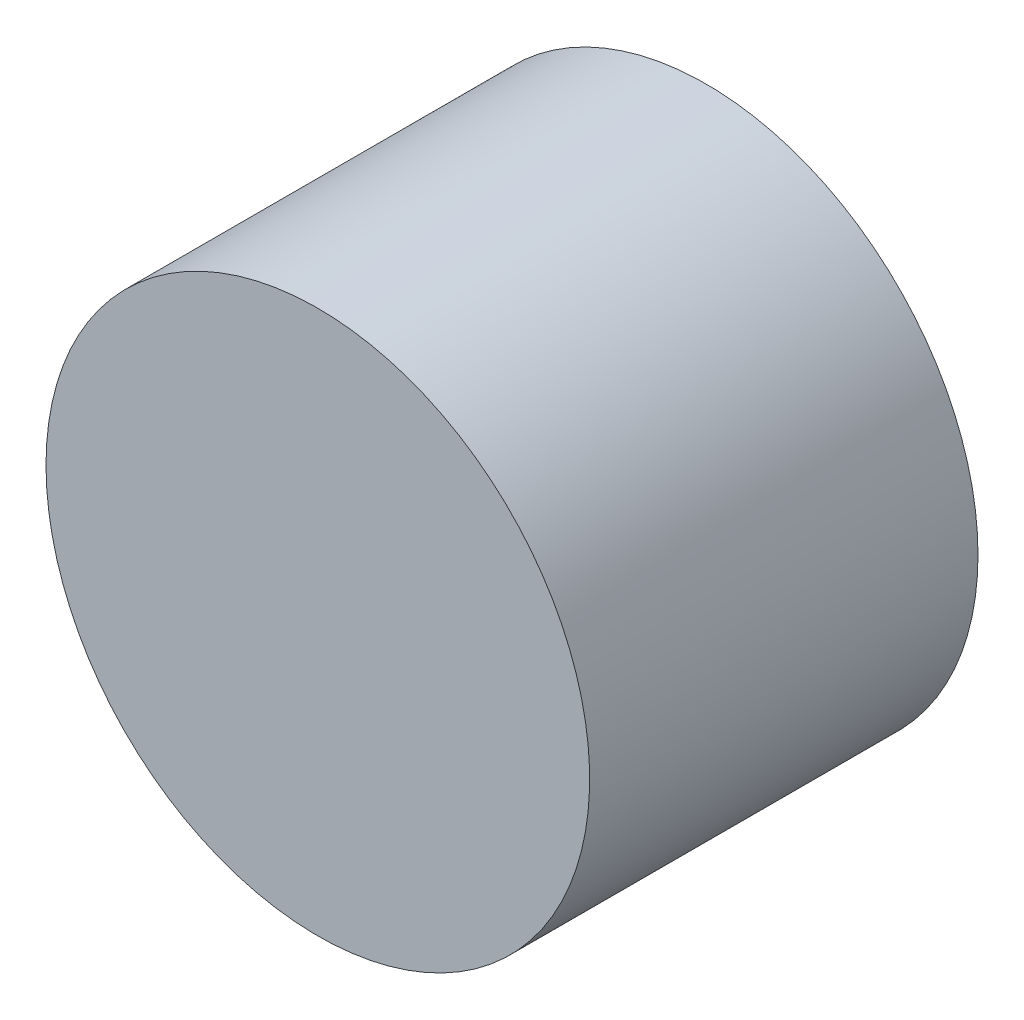
SolidWorks part; units mm, degrees
ref_plane "Plano frontal" through (0, 0, 0) normal (0, 0, 1) x (1, 0, 0)
ref_plane "Plano superior" through (0, 0, 0) normal (0, 1, 0) x (1, 0, 0)
ref_plane "Plano direito" through (0, 0, 0) normal (1, 0, 0) x (0, 0, -1)
sketch "Esboço1" plane through (0, 0, 0) normal (0, 0, 1) x (1, 0, 0)
  circle A0 centre (0, -240) radius 35 construction
  circle A1 centre (0, -240) radius 35
extrude "Ressalto-extrusão1" add sketch "Esboço1" along normal up to surface (50 mm away)
hole_wizard "Furo roscado de M101" positions "Esboço2" profile "Esboço3" tap size "M10" standard "DIN"
sketch "Esboço2" plane through (0, 0, 0) normal (0, 0, -1) x (-1, 0, 0)
  point P0 (0, -220)
  point P3 (17.3205, -250)
  point P6 (-17.3205, -250)
sketch "Esboço3" plane through (0, -220, 0) normal (1, 0, 0) x (0, 1, 0)
  line L0 (0, 0) -> (0, 30.0537)
  line L1 (0, 30.0537) -> (4.25, 27.5)
  line L2 (4.25, 27.5) -> (4.25, 0)
  line L5 (4.25, 0) -> (0, 0)
  line L10 (0, 30.0537) -> (-4.25, 27.5) construction
  line L11 (0, -6.35) -> (0, 107.95) construction
  dimension "Tap Drill Dia." = 8.5
  dimension "Tap Drill Depth" = 27.5
  dimension "Drill Angle" = 118
cosmetic thread "Rosca de furo1"
cosmetic thread "Rosca de furo2"
cosmetic thread "Rosca de furo3"
hole_wizard "Furos-guia com Ø10.0mm1" positions "Esboço4" profile "Esboço5" hole size "Ø10.0" standard "DIN"
sketch "Esboço4" plane through (0, 0, 0) normal (0, 0, -1) x (-1, 0, 0)
  point P2 (20, -230)
  point P5 (-20, -230)
  point P10 (0, 0)
sketch "Esboço5" plane through (-20, -230, 0) normal (1, 0, 0) x (0, 1, 0)
  line L0 (0, 0) -> (0, 30.5043)
  line L1 (0, 30.5043) -> (5, 27.5)
  line L2 (5, 27.5) -> (5, 0)
  line L5 (5, 0) -> (0, 0)
  line L10 (0, 30.5043) -> (-5, 27.5) construction
  line L11 (0, -6.35) -> (0, 107.95) construction
  dimension "Hole Dia." = 10
  dimension "Hole Depth" = 27.5
  dimension "Drill Angle" = 118
